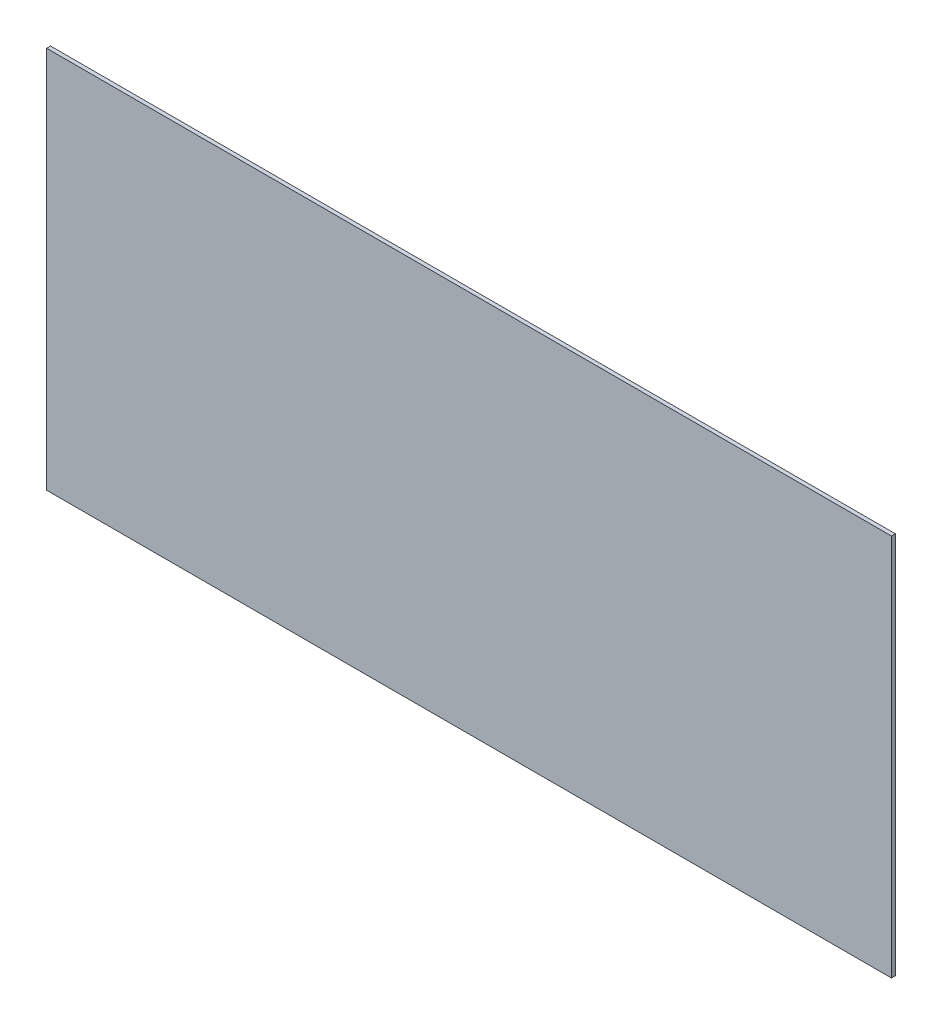
SolidWorks part; units mm, degrees
material "ABS"
ref_plane "X-Y Datum" through (0, 0, 0) normal (0, 0, 1) x (1, 0, 0)
ref_plane "X-Z Datum" through (0, 0, 0) normal (0, 1, 0) x (1, 0, 0)
ref_plane "Y-Z Datum" through (0, 0, 0) normal (1, 0, 0) x (0, 0, -1)
sketch "Sketch1" plane through (0, 0, 0) normal (0, 0, 1) x (1, 0, 0)
  line L1 (-172.76, -78.275) -> (172.76, -78.275)
  line L2 (-172.76, -78.275) -> (-172.76, 78.275)
  line L3 (-172.76, 78.275) -> (172.76, 78.275)
  line L4 (172.76, -78.275) -> (172.76, 78.275)
  line L5 (-172.76, -78.275) -> (172.76, 78.275) construction
  line L6 (-172.76, 78.275) -> (172.76, -78.275) construction
  point P0 (0, 0)
extrude "Boss-Extrude1" add sketch "Sketch1" along normal blind 1.5875
